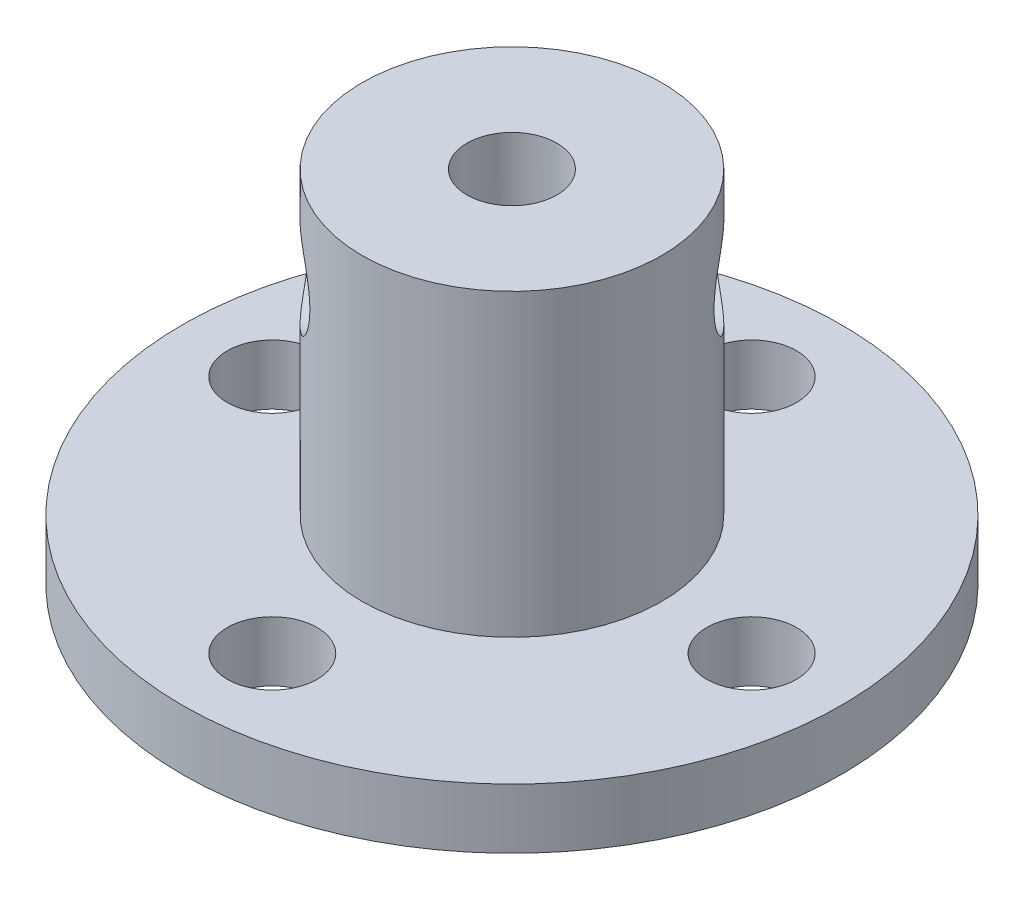
SolidWorks part; units mm, degrees
ref_plane "前基準面" through (0, 0, 0) normal (0, 0, 1) x (1, 0, 0)
ref_plane "上基準面" through (0, 0, 0) normal (0, 1, 0) x (1, 0, 0)
ref_plane "右基準面" through (0, 0, 0) normal (1, 0, 0) x (0, 0, -1)
sketch "草圖1" plane through (0, 0, 0) normal (0, 1, 0) x (1, 0, 0)
  circle A0 centre (0, 0) radius 11
  circle A1 centre (0, 0) radius 8 construction
  circle A2 centre (0, 8) radius 1.5
  circle A3 centre (8, 0) radius 1.5
  circle A4 centre (0, -8) radius 1.5
  circle A5 centre (-8, 0) radius 1.5
  point P15 (0, 0)
  dimension "D1" = 22
  dimension "D2" = 16
  dimension "D3" = 3
  dimension "D4" = 4
extrude "填料-伸長1" add sketch "草圖1" along normal blind 2
sketch "草圖2" plane through (0, 2, 0) normal (0, 1, 0) x (1, 0, 0)
  circle A0 centre (0, 0) radius 5
  dimension "D1" = 10
extrude "填料-伸長2" add sketch "草圖2" along normal blind 10
sketch "草圖3" plane through (0, 12, 0) normal (0, 1, 0) x (1, 0, 0)
  circle A0 centre (0, 0) radius 1.5
  dimension "D1" = 3
extrude "除料-伸長1" cut sketch "草圖3" against normal through all
sketch "草圖4" plane through (0, 2, 0) normal (0, 1, 0) x (1, 0, 0)
  line L1 (7.7782, -7.7782) -> (-7.7782, 7.7782)
  circle A0 centre (0, 0) radius 11 construction
ref_plane "平面1" through (0, 0, 0) normal (0.7071, 0, -0.7071) x (-0.7071, 0, -0.7071)
sketch "草圖5" plane through (0, 0, 0) normal (0.7071, 0, -0.7071) x (-0.7071, 0, -0.7071)
  line L0 (1.5, 12) -> (-1.5, 12) construction
  circle A0 centre (0, 9) radius 1.5
  dimension "D1" = 3
  dimension "D2" = 3
extrude "除料-伸長2" cut sketch "草圖5" against normal through all both and the other way through all
